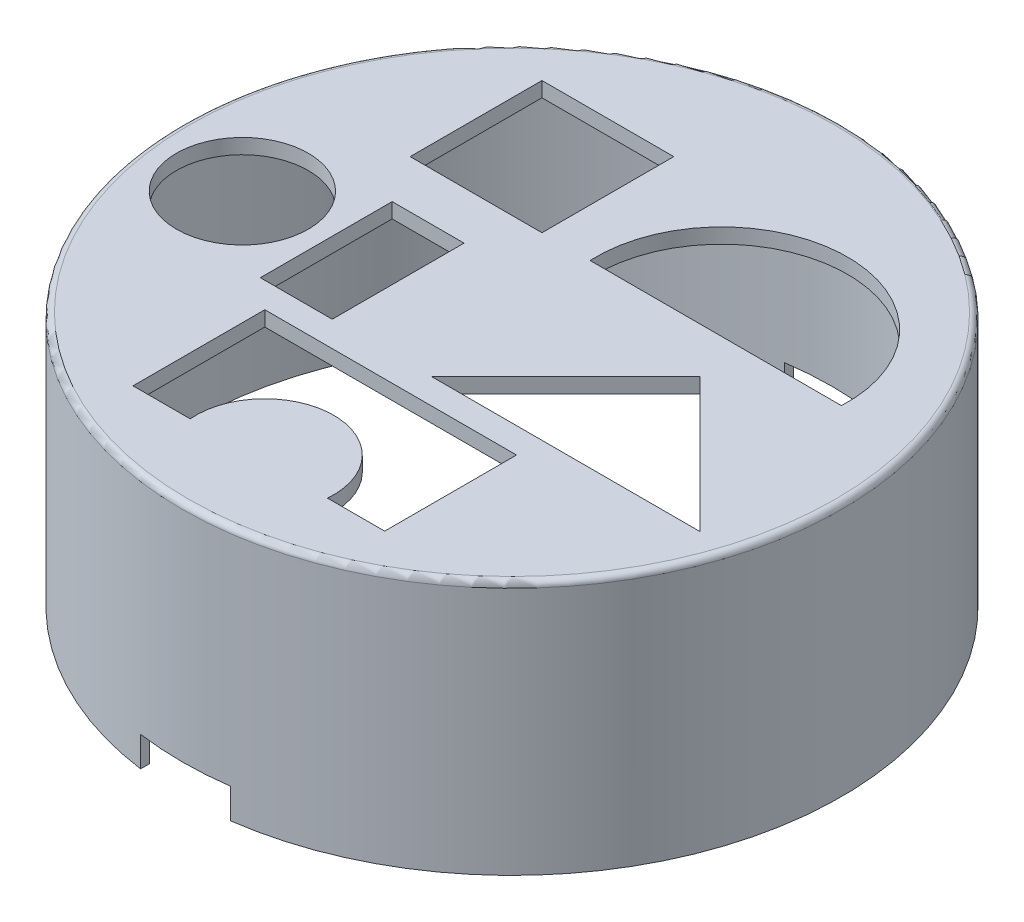
SolidWorks part; units mm, degrees
ref_plane "Front Plane" through (0, 0, 0) normal (0, 0, 1) x (1, 0, 0)
ref_plane "Top Plane" through (0, 0, 0) normal (0, 1, 0) x (1, 0, 0)
ref_plane "Right Plane" through (0, 0, 0) normal (1, 0, 0) x (0, 0, -1)
sketch "Sketch1" plane through (0, 0, 0) normal (0, 1, 0) x (1, 0, 0)
  line L0 (0, -28.75) -> (0, -21.25) construction
  line L1 (-20, -21.25) -> (20, -21.25)
  line L2 (-20, -21.25) -> (-20, -41.25)
  line L3 (-20, -41.25) -> (20, -41.25)
  line L4 (20, -21.25) -> (20, -41.25)
  line L5 (-20, -21.25) -> (20, -41.25) construction
  line L6 (-20, -41.25) -> (20, -21.25) construction
  line L7 (5, -15) -> (25, 5)
  line L10 (5, -15) -> (45, -15)
  line L12 (25, 5) -> (25, -15) construction
  line L13 (0, 15) -> (40, 15)
  line L14 (25, 5) -> (45, -15)
  line L15 (-25, 5) -> (-15, 5)
  line L16 (-25, 5) -> (-25, -15)
  line L17 (-25, -15) -> (-15, -15)
  line L18 (-15, 5) -> (-15, -15)
  line L19 (-25, 5) -> (-15, -15) construction
  line L20 (-25, -15) -> (-15, 5) construction
  line L21 (20, 15) -> (20, 35) construction
  line L23 (-30, 35) -> (-10, 35)
  line L24 (-30, 35) -> (-30, 15)
  line L25 (-30, 15) -> (-10, 15)
  line L26 (-10, 35) -> (-10, 15)
  line L27 (-30, 35) -> (-10, 15) construction
  line L28 (-30, 15) -> (-10, 35) construction
  circle A0 centre (0, 0) radius 55
  arc A1 (-12.5, -41.25) -> (12.5, -41.25) centre (0, -41.25) cw
  circle A2 centre (-40, -5) radius 10
  arc A3 (0, 15) -> (40, 15) centre (20, 15) cw
  point P3 (0, -31.25)
  point P8 (0, -25)
  point P12 (25, -5)
  point P18 (-20, -5)
  point P28 (20, 25)
  point P31 (-20, 25)
  dimension "D1" = 110
  dimension "D5" = 12.5
  dimension "D13" = 20
  dimension "D2" = 20
  dimension "D3" = 40
  dimension "D4" = 25
  dimension "D6" = 40
  dimension "D7" = 20
  dimension "D8" = 25
  dimension "D9" = 5
  dimension "D10" = 10
  dimension "D11" = 20
  dimension "D12" = 20
  dimension "D14" = 40
  dimension "D15" = 40
  dimension "D16" = 25
  dimension "D17" = 20
  dimension "D18" = 20
  dimension "D19" = 20
extrude "Boss-Extrude1" add sketch "Sketch1" along normal blind 2.5 contours A0 A2 L23 L26 L25 L24 L15 L18 L17 L16 L7 L14 L10 L1 L4 L3 L2 L13 A3 | A1 L3
sketch "Sketch2" plane through (0, 0, 0) normal (0, -1, 0) x (1, 0, 0)
  circle A1 centre (0, 0) radius 55 construction
  circle A2 centre (0, 0) radius 53.5
  circle A3 centre (0, 0) radius 53.5
  circle A4 centre (0, 0) radius 55
  dimension "D1" = 1.5
extrude "Boss-Extrude2" add sketch "Sketch2" along normal blind 40
sketch "Sketch3" plane through (0, 2.5, 0) normal (0, 1, 0) x (1, 0, 0)
  line L1 (-9, 36) -> (-31, 36)
  line L2 (0, 15) -> (40, 15)
  line L3 (0, 15) -> (40, 15)
  line L4 (25, 5) -> (5, -15)
  line L5 (45, -15) -> (25, 5)
  line L6 (5, -15) -> (45, -15)
  line L7 (25, 5) -> (5, -15)
  line L8 (45, -15) -> (25, 5)
  line L9 (5, -15) -> (45, -15)
  line L10 (-31, 36) -> (-31, 14)
  line L11 (20, -21.25) -> (-20, -21.25)
  line L12 (20, -41.25) -> (20, -21.25)
  line L13 (12.5, -41.25) -> (20, -41.25)
  line L14 (-20, -21.25) -> (-20, -41.25)
  line L15 (20, -21.25) -> (-20, -21.25)
  line L16 (20, -41.25) -> (20, -21.25)
  line L17 (12.5, -41.25) -> (20, -41.25)
  line L18 (-20, -21.25) -> (-20, -41.25)
  line L19 (-15, 5) -> (-25, 5)
  line L20 (-15, -15) -> (-15, 5)
  line L21 (-25, -15) -> (-15, -15)
  line L22 (-25, 5) -> (-25, -15)
  line L23 (-15, 5) -> (-25, 5)
  line L24 (-15, -15) -> (-15, 5)
  line L25 (-25, -15) -> (-15, -15)
  line L26 (-25, 5) -> (-25, -15)
  line L27 (-31, 14) -> (-9, 14)
  line L28 (-9, 14) -> (-9, 36)
  line L29 (-10, 35) -> (-30, 35)
  line L30 (-10, 15) -> (-10, 35)
  line L31 (-30, 15) -> (-10, 15)
  line L32 (-30, 35) -> (-30, 15)
  line L33 (-10, 35) -> (-30, 35)
  line L34 (-10, 15) -> (-10, 35)
  line L35 (-30, 15) -> (-10, 15)
  line L36 (-30, 35) -> (-30, 15)
  line L37 (-0.9762, 14) -> (40.9762, 14)
  line L38 (-14, 6) -> (-26, 6)
  line L39 (-26, 6) -> (-26, -16)
  line L40 (-26, -16) -> (-14, -16)
  line L41 (-14, -16) -> (-14, 6)
  line L42 (25, 6.4142) -> (2.5858, -16)
  line L43 (2.5858, -16) -> (47.4142, -16)
  line L44 (47.4142, -16) -> (25, 6.4142)
  line L49 (21, -20.25) -> (-21, -20.25)
  line L50 (-21, -20.25) -> (-21, -42.25)
  line L51 (-21, -42.25) -> (-11.4564, -42.25)
  line L52 (11.4564, -42.25) -> (21, -42.25)
  line L53 (21, -42.25) -> (21, -20.25)
  line L54 (-20, -41.25) -> (-12.5, -41.25)
  line L55 (-20, -41.25) -> (-12.5, -41.25)
  arc A0 (40.9762, 14) -> (-0.9762, 14) centre (20, 15) ccw
  circle A1 centre (0, 0) radius 55
  circle A2 centre (0, 0) radius 55
  circle A3 centre (-40, -5) radius 10
  circle A4 centre (-40, -5) radius 10
  arc A5 (40, 15) -> (0, 15) centre (20, 15) ccw
  arc A6 (40, 15) -> (0, 15) centre (20, 15) ccw
  circle A7 centre (-40, -5) radius 11
  arc A8 (11.4564, -42.25) -> (-11.4564, -42.25) centre (0, -41.25) ccw
  arc A9 (12.5, -41.25) -> (-12.5, -41.25) centre (0, -41.25) ccw
  arc A10 (12.5, -41.25) -> (-12.5, -41.25) centre (0, -41.25) ccw
  dimension "D1" = 0
  dimension "D2" = 0
  dimension "D3" = 0
  dimension "D4" = 0
  dimension "D5" = 0
  dimension "D6" = 0
  dimension "D7" = 0
  dimension "D8" = 1
  dimension "D9" = 1
  dimension "D10" = 1
  dimension "D11" = 1
  dimension "D12" = 1
  dimension "D13" = 1
extrude "Cut-Extrude1" cut sketch "Sketch3" against normal blind 5
fillet "Fillet1" radius 1 1 edges at (0, 2.5, 55)
fillet "Fillet2" radius 1 1 edges at (0, 0, -53.5)
sketch "Sketch4" plane through (0, 0, 0) normal (0, 0, 1) x (1, 0, 0)
  line L0 (-55, -40) -> (55, -40) construction
  line L2 (-7.5, -40) -> (-7.5, -35)
  line L3 (-7.5, -35) -> (7.5, -35)
  line L4 (7.5, -40) -> (7.5, -35)
  line L5 (0, -40) -> (7.5, -35) construction
  line L6 (-7.5, -35) -> (0, -40) construction
  line L7 (-7.5, -40) -> (7.5, -40)
  point P0 (0, -40)
  dimension "D1" = 15
  dimension "D2" = 5
extrude "Cut-Extrude2" cut sketch "Sketch4" against normal through all both and the other way through all
